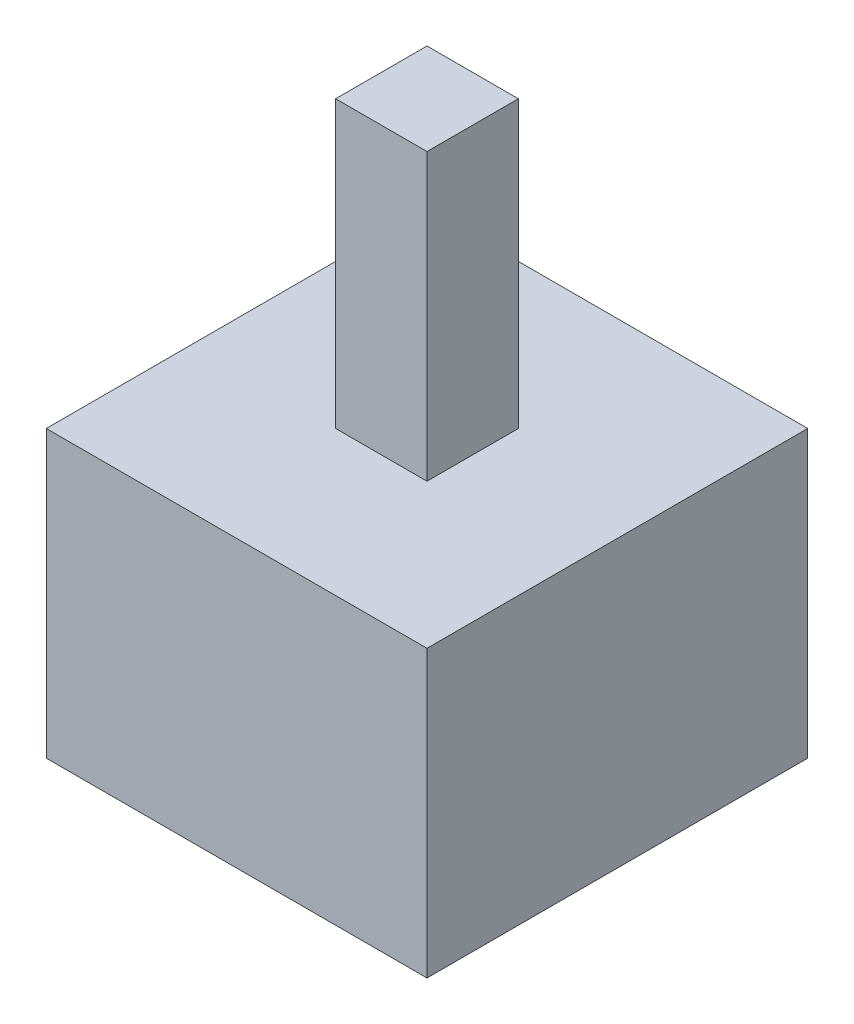
SolidWorks part; units mm, degrees
material "6061-T6 (SS)"
ref_plane "Front Plane" through (0, 0, 0) normal (0, 0, 1) x (1, 0, 0)
ref_plane "Top Plane" through (0, 0, 0) normal (0, 1, 0) x (1, 0, 0)
ref_plane "Right Plane" through (0, 0, 0) normal (1, 0, 0) x (0, 0, -1)
sketch "Sketch1" plane through (0, 0, 0) normal (0, 1, 0) x (1, 0, 0)
  line L1 (-6.35, -6.35) -> (6.35, -6.35)
  line L2 (-6.35, -6.35) -> (-6.35, 6.35)
  line L3 (-6.35, 6.35) -> (6.35, 6.35)
  line L4 (6.35, -6.35) -> (6.35, 6.35)
  line L5 (-6.35, -6.35) -> (6.35, 6.35) construction
  line L6 (-6.35, 6.35) -> (6.35, -6.35) construction
  point P0 (0, 0)
  dimension "D1" = 12.7
  dimension "D2" = 12.7
extrude "Boss-Extrude1" add sketch "Sketch1" along normal blind 9.525
sketch "Sketch3" plane through (0, 9.525, 0) normal (0, 1, 0) x (1, 0, 0)
  line L1 (-1.524, 1.524) -> (1.524, 1.524)
  line L2 (-1.524, 1.524) -> (-1.524, -1.524)
  line L3 (-1.524, -1.524) -> (1.524, -1.524)
  line L4 (1.524, 1.524) -> (1.524, -1.524)
  line L5 (-1.524, 1.524) -> (1.524, -1.524) construction
  line L6 (-1.524, -1.524) -> (1.524, 1.524) construction
  point P0 (0, 0)
  dimension "D1" = 3.048
  dimension "D2" = 3.048
extrude "Boss-Extrude2" add sketch "Sketch3" along normal blind 9.525 contours L2 L3 L4 L1
sketch "Sketch4" plane through (0, 0, 0) normal (0, -1, 0) x (1, 0, 0)
  circle A0 centre (0, 0) radius 3.175
  dimension "D1" = 6.35
extrude "Cut-Extrude1" cut sketch "Sketch4" against normal blind 6.35
